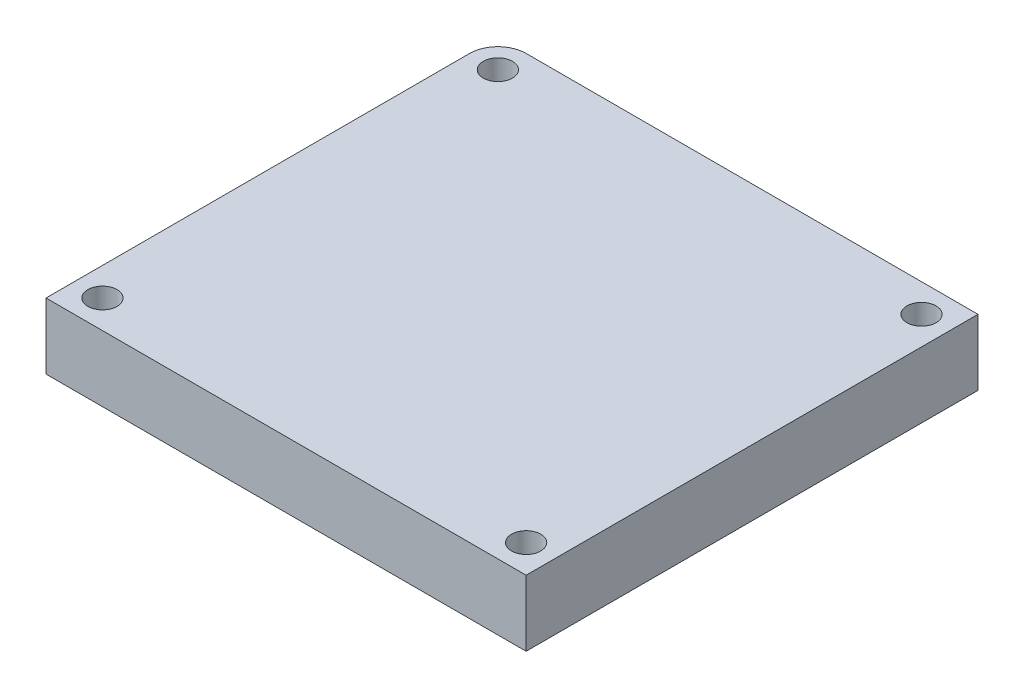
SolidWorks part; units mm, degrees
ref_plane "Front Plane" through (0, 0, 0) normal (0, 0, 1) x (1, 0, 0)
ref_plane "Top Plane" through (0, 0, 0) normal (0, 1, 0) x (1, 0, 0)
ref_plane "Right Plane" through (0, 0, 0) normal (1, 0, 0) x (0, 0, -1)
sketch "Sketch1" plane through (0, 0, 0) normal (0, 1, 0) x (1, 0, 0)
  line L0 (-67.0287, 18.4053) -> (-63.8537, 18.4053)
  line L1 (-67.0287, 18.4053) -> (-67.0287, -21.5947)
  line L2 (-67.0287, -21.5947) -> (-63.8537, -21.5947)
  line L3 (-63.8537, 18.4053) -> (-63.8537, -21.5947)
  line L4 (-74.0287, 18.4053) -> (-63.8537, 18.4053) construction
  line L5 (-74.0287, 18.4053) -> (-63.8537, 18.4053)
  line L6 (-74.0287, 18.4053) -> (-74.0287, -21.5947)
  line L7 (-74.0287, -21.5947) -> (-63.8537, -21.5947)
  line L8 (-63.8537, 18.4053) -> (-63.8537, -21.5947)
  line L9 (-74.0287, -21.5947) -> (-63.8537, 18.4053) construction
  line L10 (-46.4412, 22.4053) -> (-46.4412, 19.4053) construction
  line L11 (-94.4412, -25.5947) -> (-43.4412, -25.5947)
  line L12 (-94.4412, -25.5947) -> (-94.4412, 19.4053)
  line L13 (-91.4412, 22.4053) -> (-43.4412, 22.4053)
  line L14 (-43.4412, -25.5947) -> (-43.4412, 22.4053)
  line L15 (-94.4412, -25.5947) -> (-43.4412, 22.4053) construction
  line L16 (-94.4412, 22.4053) -> (-43.4412, -25.5947) construction
  line L17 (-46.4412, 19.4053) -> (-43.4412, 19.4053) construction
  circle A0 centre (-46.4412, 19.4053) radius 1.55
  circle A1 centre (-46.4412, -22.5947) radius 1.55
  circle A2 centre (-91.4412, -22.5947) radius 1.55
  circle A3 centre (-91.4412, 19.4053) radius 1.55
  arc A4 (-94.4412, 19.4053) -> (-91.4412, 22.4053) centre (-91.4412, 19.4053) cw
  point P5 (-68.9412, -1.5947)
  point P8 (-68.9412, -1.5947)
  dimension "D12" = 3
  dimension "D1" = 3.175
  dimension "D2" = 51
  dimension "D3" = 48
  dimension "D4" = 3
  dimension "D5" = 3
  dimension "D6" = 3
  dimension "D7" = 3
  dimension "D8" = 3
  dimension "D9" = 3
  dimension "D10" = 3
  dimension "D11" = 3
extrude "Boss-Extrude1" add sketch "Sketch1" along normal blind 7 contours L11 L14 L13 L12 A3 A2 A1 A0 L7 L6 L5 L0 L3 L2 | L6 L7 L1 L5 | L3 L0 L1 L2
